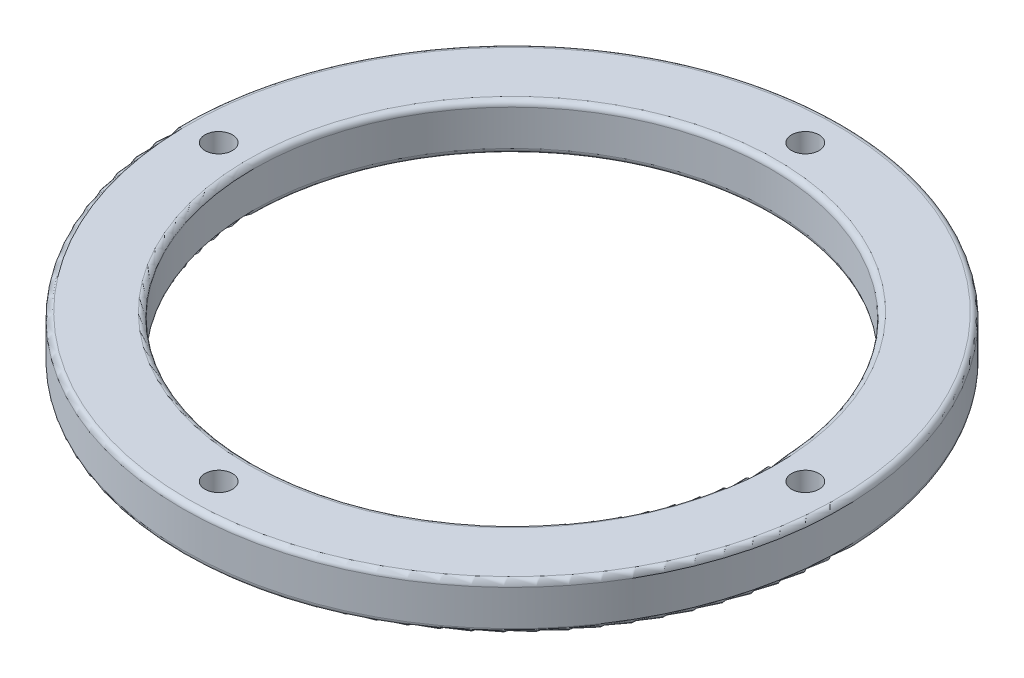
SolidWorks part; units mm, degrees
ref_plane "Front Plane" through (0, 0, 0) normal (0, 0, 1) x (1, 0, 0)
ref_plane "Top Plane" through (0, 0, 0) normal (0, 1, 0) x (1, 0, 0)
ref_plane "Right Plane" through (0, 0, 0) normal (1, 0, 0) x (0, 0, -1)
sketch "Sketch1" plane through (0, 0, 0) normal (0, 1, 0) x (1, 0, 0)
  line L0 (0, 0) -> (0, 60) construction
  circle A0 centre (0, 0) radius 47.1
  circle A1 centre (0, 0) radius 60
  circle A2 centre (0, 53.4) radius 2.5
  circle A3 centre (53.4, 0) radius 2.5
  circle A4 centre (0, -53.4) radius 2.5
  circle A5 centre (-53.4, 0) radius 2.5
  point P16 (0, 0)
  dimension "D1" = 120
  dimension "D2" = 94.2
  dimension "D4" = 5
  dimension "D3" = 53.4
  dimension "D5" = 4
extrude "Boss-Extrude1" add sketch "Sketch1" along normal blind 8.5
fillet "Fillet1" radius 1 4 edges at (0, 0, 47.1) (0, 8.5, 47.1) (0, 0, 60) (0, 8.5, 60)
